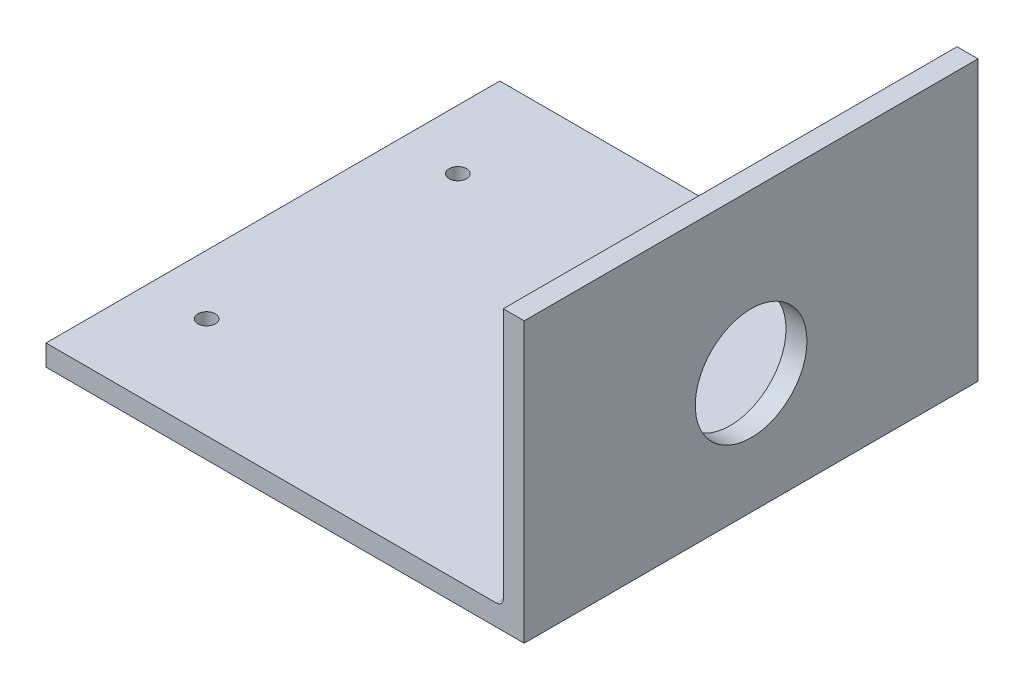
SolidWorks part; units mm, degrees
material "7075-T6 (SN)"
ref_plane "Front Plane" through (0, 0, 0) normal (0, 0, 1) x (1, 0, 0)
ref_plane "Top Plane" through (0, 0, 0) normal (0, 1, 0) x (1, 0, 0)
ref_plane "Right Plane" through (0, 0, 0) normal (1, 0, 0) x (0, 0, -1)
sketch "Sketch3" plane through (0, 863.6295, 0) normal (0, -1, 0) x (1, 0, 0)
  line L1 (652.732, 1341.8329) -> (717.732, 1341.8329)
  line L2 (652.732, 1341.8329) -> (652.732, 1276.8329)
  line L3 (652.732, 1276.8329) -> (717.732, 1276.8329)
  line L4 (717.732, 1341.8329) -> (717.732, 1276.8329)
  line L5 (652.732, 1341.8329) -> (717.732, 1276.8329) construction
  line L6 (652.732, 1276.8329) -> (717.732, 1341.8329) construction
  arc A0 (659.982, 1327.3329) -> (661.232, 1326.0829) centre (661.232, 1327.3329) ccw construction
  arc A1 (661.232, 1328.5829) -> (659.982, 1327.3329) centre (661.232, 1327.3329) ccw construction
  arc A2 (662.482, 1327.3329) -> (661.232, 1328.5829) centre (661.232, 1327.3329) ccw construction
  arc A3 (661.232, 1326.0829) -> (662.482, 1327.3329) centre (661.232, 1327.3329) ccw construction
  arc A4 (659.982, 1327.3329) -> (661.232, 1326.0829) centre (661.232, 1327.3329) ccw
  arc A5 (661.232, 1328.5829) -> (659.982, 1327.3329) centre (661.232, 1327.3329) ccw
  arc A6 (662.482, 1327.3329) -> (661.232, 1328.5829) centre (661.232, 1327.3329) ccw
  arc A7 (661.232, 1326.0829) -> (662.482, 1327.3329) centre (661.232, 1327.3329) ccw
  arc A8 (659.982, 1291.3329) -> (661.232, 1290.0829) centre (661.232, 1291.3329) ccw construction
  arc A9 (661.232, 1290.0829) -> (662.482, 1291.3329) centre (661.232, 1291.3329) ccw construction
  arc A10 (662.482, 1291.3329) -> (661.232, 1292.5829) centre (661.232, 1291.3329) ccw construction
  arc A11 (661.232, 1292.5829) -> (659.982, 1291.3329) centre (661.232, 1291.3329) ccw construction
  arc A12 (707.982, 1291.3329) -> (709.232, 1290.0829) centre (709.232, 1291.3329) ccw construction
  arc A13 (709.232, 1290.0829) -> (710.482, 1291.3329) centre (709.232, 1291.3329) ccw construction
  arc A14 (710.482, 1291.3329) -> (709.232, 1292.5829) centre (709.232, 1291.3329) ccw construction
  arc A15 (709.232, 1292.5829) -> (707.982, 1291.3329) centre (709.232, 1291.3329) ccw construction
  arc A16 (707.982, 1327.3329) -> (709.232, 1326.0829) centre (709.232, 1327.3329) ccw construction
  arc A17 (709.232, 1328.5829) -> (707.982, 1327.3329) centre (709.232, 1327.3329) ccw construction
  arc A18 (710.482, 1327.3329) -> (709.232, 1328.5829) centre (709.232, 1327.3329) ccw construction
  arc A19 (709.232, 1326.0829) -> (710.482, 1327.3329) centre (709.232, 1327.3329) ccw construction
  arc A20 (659.982, 1291.3329) -> (661.232, 1290.0829) centre (661.232, 1291.3329) ccw
  arc A21 (661.232, 1290.0829) -> (662.482, 1291.3329) centre (661.232, 1291.3329) ccw
  arc A22 (662.482, 1291.3329) -> (661.232, 1292.5829) centre (661.232, 1291.3329) ccw
  arc A23 (661.232, 1292.5829) -> (659.982, 1291.3329) centre (661.232, 1291.3329) ccw
  arc A24 (707.982, 1291.3329) -> (709.232, 1290.0829) centre (709.232, 1291.3329) ccw
  arc A25 (709.232, 1290.0829) -> (710.482, 1291.3329) centre (709.232, 1291.3329) ccw
  arc A26 (710.482, 1291.3329) -> (709.232, 1292.5829) centre (709.232, 1291.3329) ccw
  arc A27 (709.232, 1292.5829) -> (707.982, 1291.3329) centre (709.232, 1291.3329) ccw
  arc A28 (707.982, 1327.3329) -> (709.232, 1326.0829) centre (709.232, 1327.3329) ccw
  arc A29 (709.232, 1328.5829) -> (707.982, 1327.3329) centre (709.232, 1327.3329) ccw
  arc A30 (710.482, 1327.3329) -> (709.232, 1328.5829) centre (709.232, 1327.3329) ccw
  arc A31 (709.232, 1326.0829) -> (710.482, 1327.3329) centre (709.232, 1327.3329) ccw
  point P0 (685.232, 1309.3329)
  dimension "D1" = 65
  dimension "D2" = 65
extrude "Boss-Extrude2" add sketch "Sketch3" along normal blind 3
sketch "Sketch4" plane through (0, 0, 1276.8329) normal (0, 0, -1) x (-1, 0, 0)
  line L0 (-717.732, 860.6295) -> (-717.732, 863.6295) construction
  line L1 (-717.732, 860.6295) -> (-717.732, 863.6295)
  line L2 (-717.732, 863.6295) -> (-718.232, 863.6295)
  line L3 (-718.232, 863.6295) -> (-718.232, 900.6295)
  line L4 (-718.232, 900.6295) -> (-721.232, 900.6295)
  line L5 (-721.232, 900.6295) -> (-721.232, 860.6295)
  line L6 (-721.232, 860.6295) -> (-717.732, 860.6295)
  line L7 (-652.732, 860.6295) -> (-652.732, 863.6295) construction
  dimension "D1" = 0.5
  dimension "D2" = 40
extrude "Boss-Extrude3" add sketch "Sketch4" against normal up to surface (65 mm away) up to face at (685.232, 862.1295, 1341.8329)
sketch "Sketch6" plane through (721.232, 0, 0) normal (1, 0, 0) x (0, 0, -1)
  arc A0 (-1309.3329, 871.8795) -> (-1309.3329, 883.8795) centre (-1309.3329, 877.8795) ccw construction
  arc A1 (-1309.3329, 883.8795) -> (-1309.3329, 871.8795) centre (-1309.3329, 877.8795) ccw construction
  arc A2 (-1309.3329, 871.8795) -> (-1309.3329, 883.8795) centre (-1309.3329, 877.8795) ccw construction
  arc A3 (-1309.3329, 883.8795) -> (-1309.3329, 871.8795) centre (-1309.3329, 877.8795) ccw construction
  circle A4 centre (-1309.3329, 877.8795) radius 8
  dimension "D1" = 16
extrude "Cut-Extrude1" cut sketch "Sketch6" against normal up to next
fillet "Fillet1" radius 1 1 edges at (718.232, 863.6295, 1309.3329)
ref_plane "Plane1" through (0, 0, 1309.3329) normal (0, 0, 1) x (1, 0, 0)
